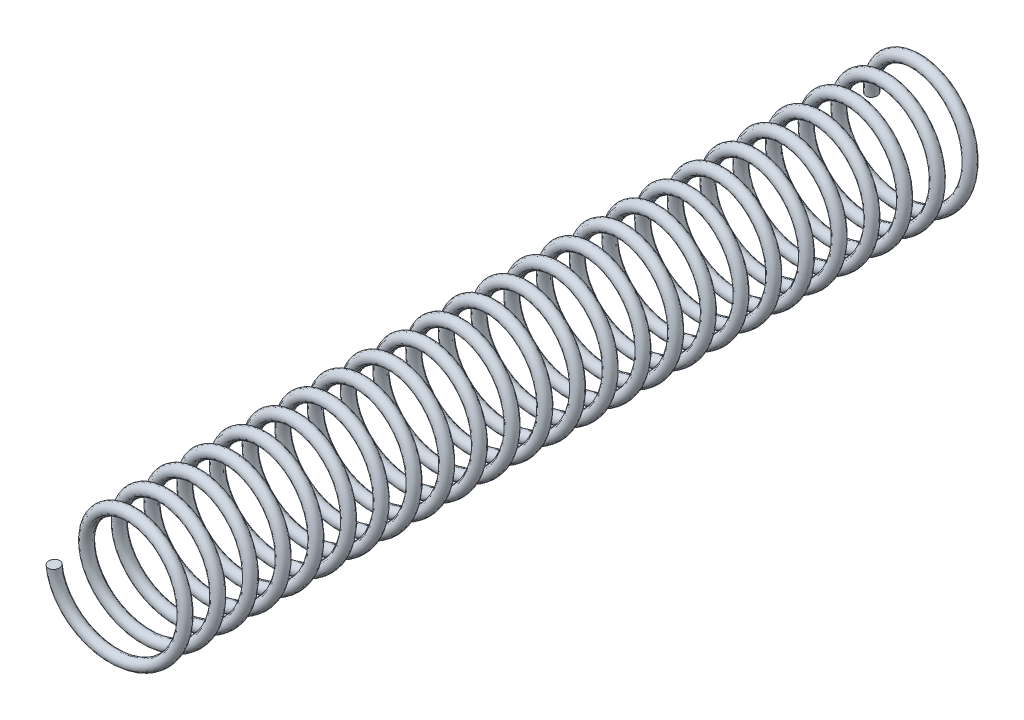
SolidWorks part; units mm, degrees
ref_plane "Спереди" through (0, 0, 0) normal (0, 0, 1) x (1, 0, 0)
ref_plane "Сверху" through (0, 0, 0) normal (0, 1, 0) x (1, 0, 0)
ref_plane "Справа" through (0, 0, 0) normal (1, 0, 0) x (0, 0, -1)
sketch "Эскиз1" plane through (0, 0, 0) normal (0, 0, 1) x (1, 0, 0)
  circle A0 centre (0, 0) radius 3.5
  dimension "D1" = 7
curve "Спираль1" pitch 2 height 50 turns 25
sweep "По траектории1" add path "Спираль1" circular profile diameter 0.7 parameters "D3"=0.7
